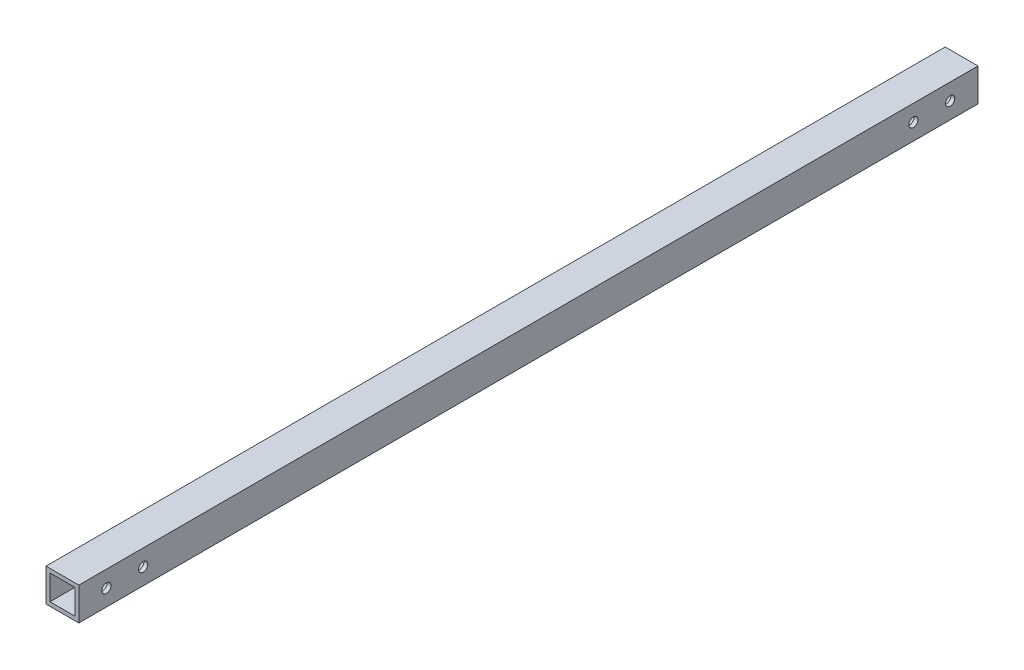
SolidWorks part; units mm, degrees
ref_plane "前视基准面" through (0, 0, 0) normal (0, 0, 1) x (1, 0, 0)
ref_plane "上视基准面" through (0, 0, 0) normal (0, 1, 0) x (1, 0, 0)
ref_plane "右视基准面" through (0, 0, 0) normal (1, 0, 0) x (0, 0, -1)
sketch "草图1" plane through (0, 0, 0) normal (0, 0, 1) x (1, 0, 0)
  line L1 (0, 0) -> (25, 0)
  line L2 (0, 0) -> (0, -25)
  line L3 (0, -25) -> (25, -25)
  line L4 (25, 0) -> (25, -25)
  line L5 (3, -3) -> (22, -3)
  line L6 (3, -3) -> (3, -22)
  line L7 (3, -22) -> (22, -22)
  line L8 (22, -3) -> (22, -22)
  dimension "D1" = 3
  dimension "D2" = 3
  dimension "D3" = 3
  dimension "D4" = 3
  dimension "D5" = 25
  dimension "D6" = 25
extrude "拉伸1" add sketch "草图1" along normal blind 684.5
hole_wizard "Ø7.0 (7) 直径孔1" positions "草图3" profile "草图4" hole size "Ø7.0" standard "GB" end condition through all
sketch "草图3" plane through (25, 0, 0) normal (1, 0, 0) x (0, 0, -1)
  line L1 (-684.5, -25) -> (0, -25) construction
  line L2 (-684.5, -25) -> (-684.5, 0) construction
  point P1 (-635.5, -12.5)
  point P3 (-663.5, -12.5)
  dimension "D1" = 21
  dimension "D2" = 28
  dimension "D3" = 12.5
sketch "草图4" plane through (25, -12.5, 635.5) normal (0, 1, 0) x (0, 0, -1)
  line L0 (0, 0) -> (0, 25)
  line L1 (0, 25) -> (3.5, 25)
  line L2 (3.5, 25) -> (3.5, 0)
  line L5 (3.5, 0) -> (0, 0)
  line L11 (0, -6.35) -> (0, 107.95) construction
  dimension "通孔孔直径" = 7
  dimension "通孔孔深度" = 25
pattern_linear "阵列(线性)1" count 2 spacing 614.32 along (0, 0, -1) of "Ø7.0 (7) 直径孔1"
